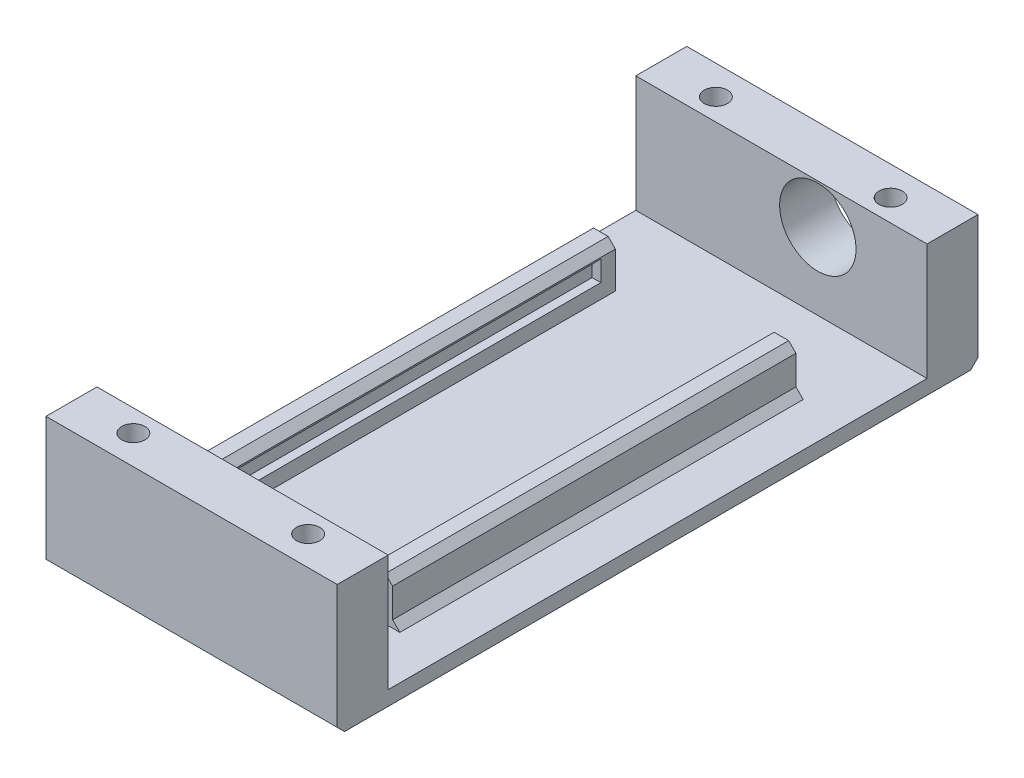
SolidWorks part; units mm, degrees
ref_plane "Alzado" through (0, 0, 0) normal (0, 0, 1) x (1, 0, 0)
ref_plane "Planta" through (0, 0, 0) normal (0, 1, 0) x (1, 0, 0)
ref_plane "Vista lateral" through (0, 0, 0) normal (1, 0, 0) x (0, 0, -1)
sketch "Croquis1" plane through (0, 0, 0) normal (0, 1, 0) x (1, 0, 0)
  line L0 (0, 0) -> (0, 50000) construction
  line L1 (-20, 44) -> (20, 44)
  line L2 (-20, 44) -> (-20, -44)
  line L3 (-20, -44) -> (20, -44)
  line L4 (20, 44) -> (20, -44)
  line L5 (-20, 44) -> (20, -44) construction
  line L6 (-20, -44) -> (20, 44) construction
  line L7 (0, 0) -> (50000, 0) construction
  circle A0 centre (-12, 40) radius 1.6
  circle A1 centre (12, 40) radius 1.6
  circle A2 centre (-12, -40) radius 1.6
  circle A3 centre (12, -40) radius 1.6
  point P0 (0, 0)
  dimension "D4" = 3.2
  dimension "D1" = 40
  dimension "D2" = 88
  dimension "D3" = 24
  dimension "D5" = 4
extrude "Saliente-Extruir1" add sketch "Croquis1" along normal blind 18
sketch "Croquis2" plane through (0, 18, 0) normal (0, 1, 0) x (1, 0, 0)
  line L0 (20, -44) -> (20, 44) construction
  line L1 (-13, 24) -> (10.2, 24) construction
  line L2 (-13, 24) -> (-13, -27.4) construction
  line L3 (-13, -27.4) -> (10.2, -27.4) construction
  line L4 (10.2, 24) -> (10.2, -27.4) construction
  line L5 (-13, 24) -> (10.2, -27.4) construction
  line L6 (-13, -27.4) -> (10.2, 24) construction
  line L7 (0.6, 54.7934) -> (9.4, 54.7934) construction
  line L8 (0.6, 54.7934) -> (0.6, 9.4014) construction
  line L9 (0.6, 9.4014) -> (9.4, 9.4014) construction
  line L10 (9.4, 54.7934) -> (9.4, 9.4014) construction
  line L11 (0.6, 54.7934) -> (9.4, 9.4014) construction
  line L12 (0.6, 9.4014) -> (9.4, 54.7934) construction
  line L13 (20, 44) -> (-20, 44) construction
  point P4 (-1.4, -1.7)
  point P9 (5, 32.0974)
  point P10 (6.6381, 54.7934)
  point P11 (0, 0)
  point P12 (0, 0)
  dimension "D1" = 51.4
  dimension "D2" = 23.2
  dimension "D3" = 0.8
  dimension "D4" = 8.8
  dimension "D5" = 15
  dimension "D6" = 20
sketch "Croquis3" plane through (0, 18, 0) normal (0, 1, 0) x (1, 0, 0)
  line L0 (-20, 44) -> (-20, -44) construction
  line L1 (-20, 37) -> (20, 37)
  line L2 (-20, 37) -> (-20, -37)
  line L3 (-20, -37) -> (20, -37)
  line L4 (20, 37) -> (20, -37)
  line L5 (-20, 37) -> (20, -37) construction
  line L6 (-20, -37) -> (20, 37) construction
  line L7 (20, -44) -> (20, 44) construction
  line L8 (20, 44) -> (-20, 44) construction
  point P4 (0, 0)
  point P12 (0, 0)
  dimension "D1" = 7
extrude "Cortar-Extruir1" cut sketch "Croquis3" against normal offset from surface (16 mm away) 2 up to face at (0, 0, 0)
sketch "Croquis4" plane through (0, 2, 0) normal (0, 1, 0) x (1, 0, 0)
  line L0 (-13, 24) -> (-13, -27.4) construction
  line L1 (-15.8, 26) -> (-11.8, 26)
  line L2 (-15.8, 26) -> (-15.8, -29.4)
  line L3 (-15.8, -29.4) -> (-11.8, -29.4)
  line L4 (-11.8, 26) -> (-11.8, -29.4)
  line L5 (-15.8, 26) -> (-11.8, -29.4) construction
  line L6 (-15.8, -29.4) -> (-11.8, 26) construction
  line L7 (-13, 24) -> (10.2, 24) construction
  line L8 (-13, -27.4) -> (10.2, -27.4) construction
  line L9 (-1.4, -1.7) -> (-1.4, 49998.3) construction
  line L10 (-1.4, -1.7) -> (49998.6, -1.7) construction
  point P4 (-13.8, -1.7)
  dimension "D1" = 1.2
  dimension "D2" = 2
  dimension "D3" = 4
  dimension "D4" = 2
extrude "Saliente-Extruir2" add sketch "Croquis4" along normal blind 6
sketch "Croquis5" plane through (0, 0, 29.4) normal (0, 0, 1) x (1, 0, 0)
  line L0 (-11.8, 4) -> (-13, 4)
  line L1 (-11.8, 8) -> (-11.8, 2) construction
  line L2 (-13, 5.6) -> (-11.8, 6.8)
  line L3 (-13, 4) -> (-13, 5.6)
  line L4 (-11.8, 4) -> (-11.8, 6.8)
  line L5 (20, 2) -> (-20, 2) construction
  point P8 (-12.9754, 4.4388)
  point P9 (0, 0)
  point P10 (-11.8, 5.1001)
  dimension "D1" = 2
  dimension "D2" = 45
  dimension "D3" = 1.6
  dimension "D4" = 1.2
extrude "Cortar-Extruir2" cut sketch "Croquis5" against normal offset from surface (51.4 mm away) 2 from offset 2 up to face at (-13.8, 5, -26) offset against normal yes
ref_plane "Plano1" through (-1.4, 0, 0) normal (1, 0, 0) x (0, 0, -1)
mirror "Simetría1" about plane through (-1.4, 0, 0) normal (1, 0, 0) of "Cortar-Extruir2", "Saliente-Extruir2"
sketch "Croquis6" plane through (0, 0, -44) normal (0, 0, -1) x (-1, 0, 0)
  line L0 (-9, 4) -> (-10.2, 4) construction
  circle A0 centre (-5, 12.5) radius 5.25
  point P5 (0, 0)
  point P6 (0, 0)
  dimension "D2" = 10.5
  dimension "D1" = 8.5
extrude "Cortar-Extruir3" cut sketch "Croquis6" against normal up to next
chamfer "Chaflán1" distance 1 angle 45 6 edges at (-15.8, 8, 1.7) (-15.8, 2, 1.7) (13, 2, 1.7) (13, 8, 1.7) (9, 8, 1.7) (-11.8, 8, 1.7)
sketch "Croquis7" plane through (0, 0, -44) normal (0, 0, -1) x (-1, 0, 0)
  line L2 (14.2278, 14.3433) -> (7.3275, 14.3433) construction
  line L3 (14.2278, 14.3433) -> (14.2278, 9.9397) construction
  line L4 (14.2278, 9.9397) -> (7.3275, 9.9397) construction
  line L5 (7.3275, 14.3433) -> (7.3275, 9.9397) construction
  line L6 (14.2278, 14.3433) -> (7.3275, 9.9397) construction
  line L7 (14.2278, 9.9397) -> (7.3275, 14.3433) construction
  text T0 "12V"
  point P0 (14.2278, 14.3433)
  point P8 (10.7776, 12.1415)
extrude "Cortar-Extruir4" cut sketch "Croquis7" against normal blind 1
chamfer "Chaflán2" distance 1 angle 45 2 edges at (0, 0, -44) (0, 0, 44)
sketch "Croquis8" plane through (0, 0, 0) normal (0, -1, 0) x (1, 0, 0)
  circle A0 centre (-12, 40) radius 2.8
  circle A1 centre (12, 40) radius 2.8
  circle A2 centre (-12, -40) radius 2.8
  circle A3 centre (12, -40) radius 2.8
  dimension "D1" = 5.6
extrude "Cortar-Extruir5" cut sketch "Croquis8" against normal blind 3.5
